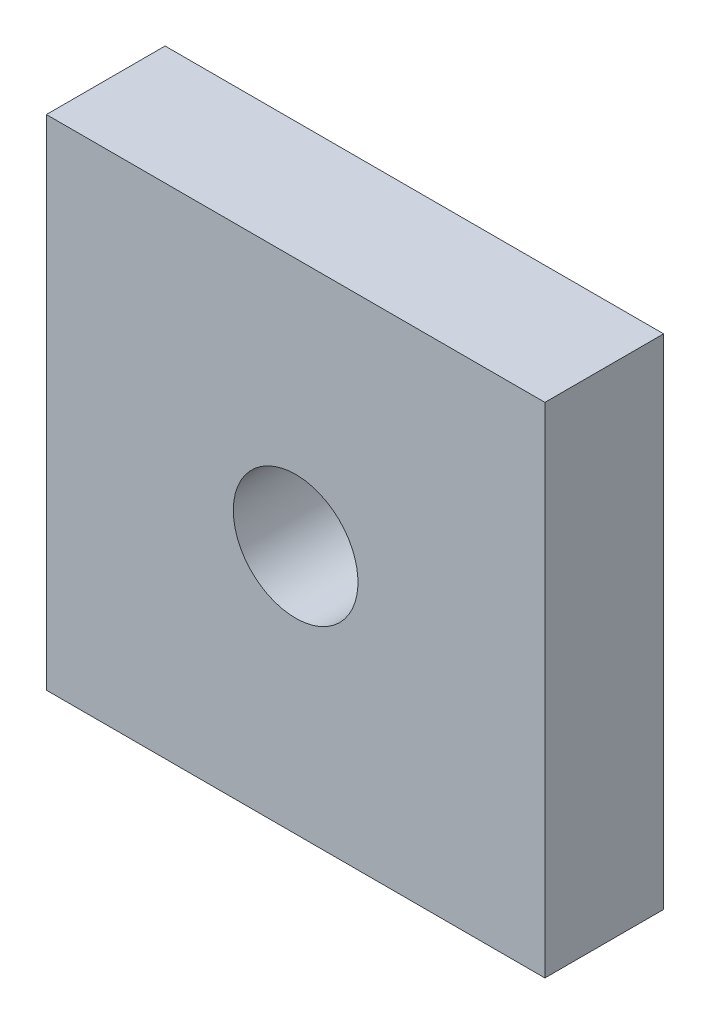
SolidWorks part; units mm, degrees
material "6061-T6 (SS)"
ref_plane "Front Plane" through (0, 0, 0) normal (0, 0, 1) x (1, 0, 0)
ref_plane "Top Plane" through (0, 0, 0) normal (0, 1, 0) x (1, 0, 0)
ref_plane "Right Plane" through (0, 0, 0) normal (1, 0, 0) x (0, 0, -1)
sketch "Sketch1" plane through (0, 0, 0) normal (0, 0, 1) x (1, 0, 0)
  line L0 (10, 10) -> (-10, -10) construction
  line L1 (-10, -10) -> (10, -10)
  line L2 (-10, -10) -> (-10, 10)
  line L3 (-10, 10) -> (10, 10)
  line L4 (10, -10) -> (10, 10)
  circle A0 centre (0, 0) radius 2.5
  point P7 (0, 0)
  dimension "D2" = 5
  dimension "D1" = 20
extrude "Boss-Extrude1" add sketch "Sketch1" along normal blind 4.7625
